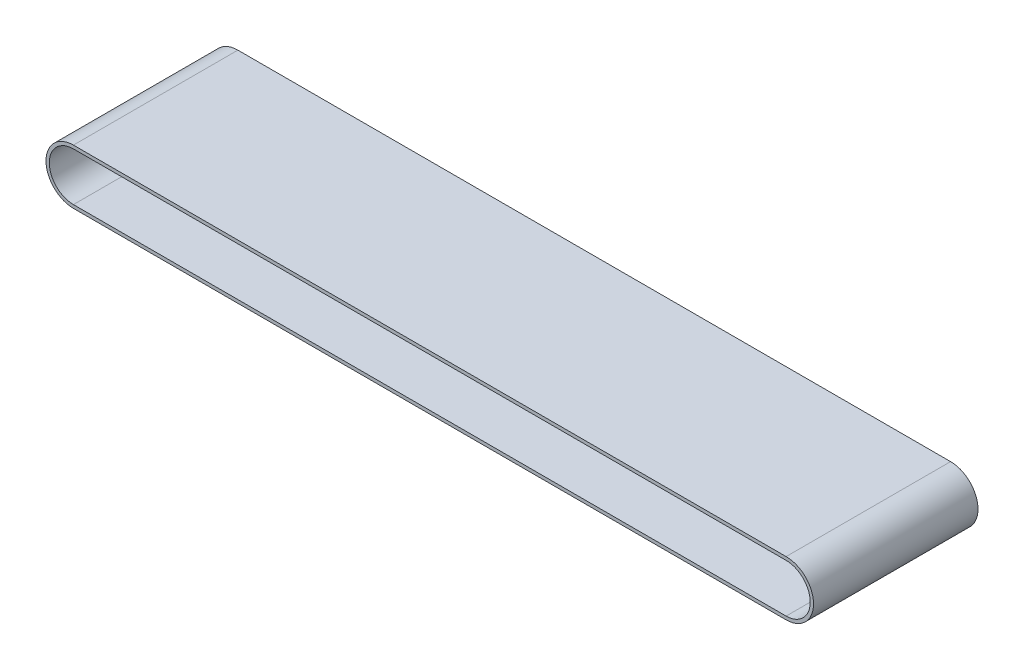
SolidWorks part; units mm, degrees
material "PVC皮带"
ref_plane "Front Plane" through (0, 0, 0) normal (0, 0, 1) x (1, 0, 0)
ref_plane "Top Plane" through (0, 0, 0) normal (0, 1, 0) x (1, 0, 0)
ref_plane "Right Plane" through (0, 0, 0) normal (1, 0, 0) x (0, 0, -1)
sketch "Sketch1" plane through (0, 0, 0) normal (0, 0, 1) x (1, 0, 0)
  line L0 (0, 0) -> (1300, 0) construction
  line L1 (0, 50) -> (1300, 50)
  line L2 (0, -50) -> (1300, -50)
  line L3 (0, 0) -> (149.2779, 0)
  line L4 (0, 44) -> (1300, 44)
  line L5 (0, -44) -> (1300, -44)
  arc A0 (0, 50) -> (0, -50) centre (0, 0) ccw
  arc A1 (1300, -50) -> (1300, 50) centre (1300, 0) ccw
  arc A2 (1300, -44) -> (1300, 44) centre (1300, 0) ccw
  arc A3 (0, 44) -> (0, -44) centre (0, 0) ccw
  point P3 (650, 0)
  dimension "D2" = 50
  dimension "D1" = 0
  dimension "D3" = 1300
  dimension "D4" = 6
extrude "Boss-Extrude1" add sketch "Sketch1" along normal mid plane 300 contours L2 A1 L1 A0 A3 L4 A2 L5
